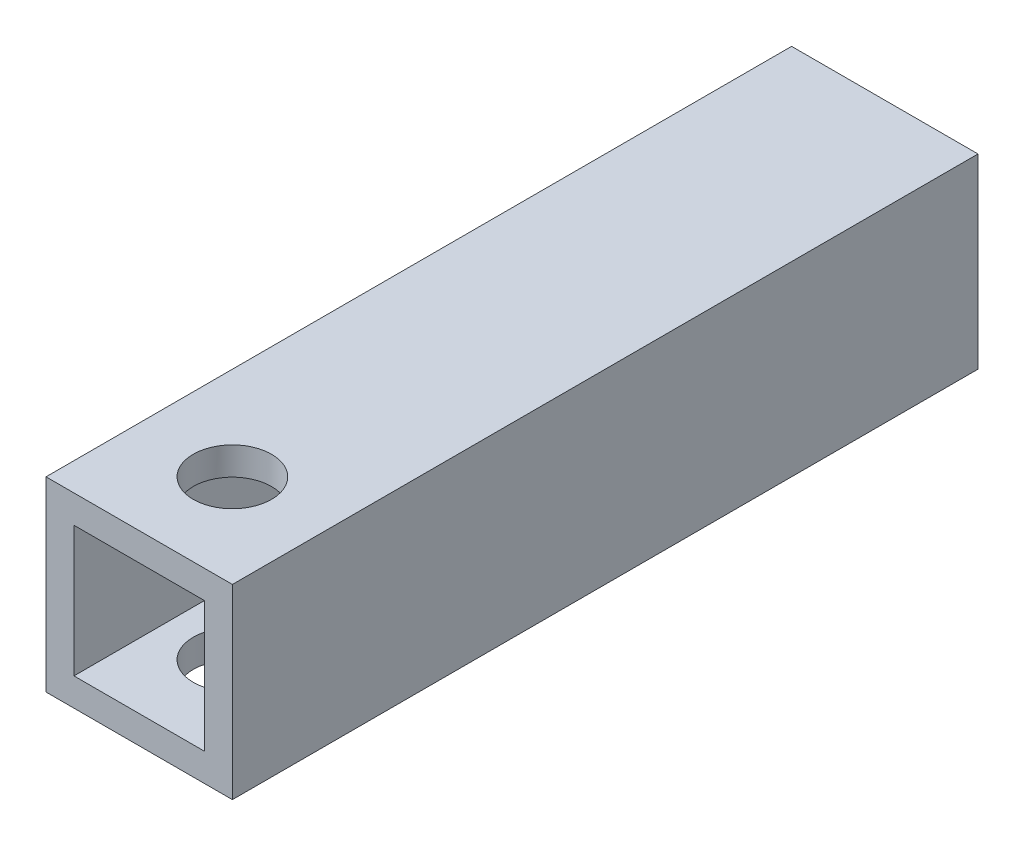
SolidWorks part; units mm, degrees
ref_plane "前基準面" through (0, 0, 0) normal (0, 0, 1) x (1, 0, 0)
ref_plane "上基準面" through (0, 0, 0) normal (0, 1, 0) x (1, 0, 0)
ref_plane "右基準面" through (0, 0, 0) normal (1, 0, 0) x (0, 0, -1)
sketch "草圖1" plane through (0, 0, 0) normal (0, 0, 1) x (1, 0, 0)
  line L1 (-5, -5) -> (5, -5)
  line L2 (-5, -5) -> (-5, 5)
  line L3 (-5, 5) -> (5, 5)
  line L4 (5, -5) -> (5, 5)
  line L5 (-5, -5) -> (5, 5) construction
  line L6 (-5, 5) -> (5, -5) construction
  point P0 (0, 0)
  dimension "D1" = 10
extrude "伸長-薄件1" add sketch "草圖1" along normal blind 40 thin thin type one direction reverse wall 1.5
hole_wizard "M5 螺紋孔1" positions "草圖2" profile "草圖3" tap size "M5" standard "ISO" end condition through all
sketch "草圖2" plane through (0, 5, 0) normal (0, 1, 0) x (1, 0, 0)
  line L0 (5, -40) -> (-5, -40) construction
  point P0 (0, -35)
  dimension "D1" = 5
sketch "草圖3" plane through (0, 5, 35) normal (1, 0, 0) x (0, 0, 1)
  line L0 (0, 0) -> (0, 10)
  line L1 (0, 10) -> (2.1, 10)
  line L2 (2.1, 10) -> (2.1, 0)
  line L5 (2.1, 0) -> (0, 0)
  line L11 (0, -6.35) -> (0, 107.95) construction
  dimension "貫穿螺孔鑽直徑" = 4.2
  dimension "貫穿螺孔鑽深度" = 10
